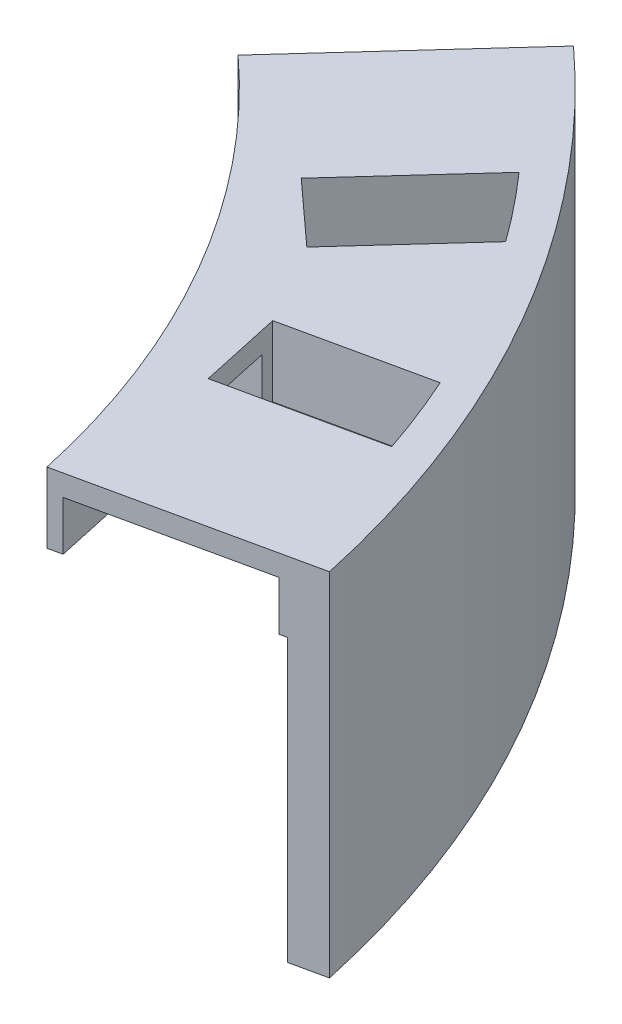
SolidWorks part; units mm, degrees
ref_plane "Front Plane" through (0, 0, 0) normal (0, 0, 1) x (1, 0, 0)
ref_plane "Top Plane" through (0, 0, 0) normal (0, 1, 0) x (1, 0, 0)
ref_plane "Right Plane" through (0, 0, 0) normal (1, 0, 0) x (0, 0, -1)
sketch "Sketch1" plane through (0, 157.2797, 0) normal (0, 1, 0) x (1, 0, 0)
  line L8 (293.0357, -316.1992) -> (265.929, -322.1104) construction
  line L9 (228.8196, -257.8351) -> (247.4922, -237.3156) construction
  line L10 (263.206, -252.2864) -> (248.4548, -268.4966) construction
  line L11 (248.4548, -268.4966) -> (257.3301, -276.573) construction
  line L12 (257.3301, -276.573) -> (270.7909, -261.7809) construction
  line L13 (283.4975, -283.7893) -> (263.9567, -288.0506) construction
  line L14 (263.9567, -288.0506) -> (266.5135, -299.7751) construction
  line L15 (266.5135, -299.7751) -> (287.9275, -295.1053) construction
  line L24 (293.0357, -316.1992) -> (265.929, -322.1104)
  line L25 (228.8196, -257.8351) -> (247.4922, -237.3156)
  line L26 (263.206, -252.2864) -> (248.4548, -268.4966)
  line L27 (248.4548, -268.4966) -> (257.3301, -276.573)
  line L28 (257.3301, -276.573) -> (270.7909, -261.7809)
  line L29 (283.4975, -283.7893) -> (263.9567, -288.0506)
  line L30 (263.9567, -288.0506) -> (266.5135, -299.7751)
  line L31 (266.5135, -299.7751) -> (287.9275, -295.1053)
  arc A0 (263.206, -252.2864) -> (247.4922, -237.3156) centre (169.4518, -334.9614) ccw construction
  arc A1 (283.4975, -283.7893) -> (270.7909, -261.7809) centre (169.4518, -334.9614) ccw construction
  arc A2 (293.0357, -316.1992) -> (287.9275, -295.1053) centre (169.4518, -334.9614) ccw construction
  arc A3 (263.206, -252.2864) -> (247.4922, -237.3156) centre (169.4518, -334.9614) ccw
  arc A4 (283.4975, -283.7893) -> (270.7909, -261.7809) centre (169.4518, -334.9614) ccw
  arc A5 (293.0357, -316.1992) -> (287.9275, -295.1053) centre (169.4518, -334.9614) ccw
  arc A6 (265.929, -322.1104) -> (228.8196, -257.8351) centre (146.6616, -348.1193) ccw
extrude "Boss-Extrude1" add sketch "Sketch1" along normal blind 10
sketch "Sketch2" plane through (0, 157.2797, 0) normal (0, 1, 0) x (1, 0, 0)
  line L0 (267.8229, -321.6974) -> (265.2661, -309.973)
  line L1 (293.0357, -316.1992) -> (265.929, -322.1104) construction
  line L2 (265.2661, -309.973) -> (295.5543, -303.368)
  line L3 (267.8229, -321.6974) -> (297.9305, -315.1318)
  line L4 (297.9305, -315.1318) -> (295.5543, -303.368)
  line L5 (228.8196, -257.8351) -> (247.4922, -237.3156) construction
  line L6 (251.0299, -233.428) -> (230.1657, -256.3559)
  line L7 (251.0299, -233.428) -> (259.9051, -241.5045)
  line L8 (259.9051, -241.5045) -> (239.041, -264.4323)
  line L9 (230.1657, -256.3559) -> (239.041, -264.4323)
  arc A1 (293.0357, -316.1992) -> (287.9275, -295.1053) centre (169.4518, -334.9614) ccw construction
  arc A3 (263.206, -252.2864) -> (247.4922, -237.3156) centre (169.4518, -334.9614) ccw construction
  dimension "D1" = 12
  dimension "D2" = 31
  dimension "D3" = 130
  dimension "D4" = 130
  dimension "D5" = 31
  dimension "D6" = 12
  dimension "D7" = 0
  dimension "D8" = 130
extrude "Cut-Extrude1" cut sketch "Sketch2" along normal blind 7
sketch "Sketch3" plane through (0, 167.2797, 0) normal (0, 1, 0) x (1, 0, 0)
  line L0 (293.0357, -316.1992) -> (298.8979, -314.9208)
  line L4 (251.5304, -232.878) -> (247.4922, -237.3156)
  arc A0 (251.5304, -232.878) -> (298.8979, -314.9208) centre (146.6616, -348.1193) cw
  arc A1 (248.1652, -236.576) -> (294.0127, -315.9862) centre (172.7112, -333.0795) cw construction
  arc A3 (247.4922, -237.3156) -> (293.0357, -316.1992) centre (169.4518, -334.9614) cw
  dimension "D5" = 122.5
  dimension "D1" = 6
  dimension "D2" = 6
  dimension "D3" = 1
  dimension "D4" = 1
  dimension "D6" = 6
extrude "Boss-Extrude2" add sketch "Sketch3" against normal blind 50
sketch "Sketch4" plane through (0, 117.2797, 0) normal (0, -1, 0) x (1, 0, 0)
  line L0 (293.0357, 316.1992) -> (294.0127, 315.9862)
  line L1 (293.0357, 316.1992) -> (298.8979, 314.9208) construction
  line L2 (247.4922, 237.3156) -> (248.1652, 236.576)
  line L3 (251.5304, 232.878) -> (247.4922, 237.3156) construction
  arc A0 (293.0357, 316.1992) -> (247.4922, 237.3156) centre (169.4518, 334.9614) cw
  arc A1 (248.1652, 236.576) -> (294.0127, 315.9862) centre (168.9131, 335.2723) ccw
  dimension "D1" = 1
  dimension "D2" = 1
extrude "Cut-Extrude2" cut sketch "Sketch4" against normal blind 40
sketch "Sketch5" plane through (0, 157.2797, 0) normal (0, 1, 0) x (1, 0, 0)
  line L0 (249.934, -269.8427) -> (255.8509, -275.227)
  line L1 (257.3301, -276.573) -> (248.4548, -268.4966) construction
  line L2 (249.934, -269.8427) -> (248.4548, -268.4966) construction
  line L3 (255.8509, -275.227) -> (257.3301, -276.573) construction
  line L4 (249.934, -269.8427) -> (243.2037, -277.2387)
  line L5 (255.8509, -275.227) -> (249.1205, -282.623)
  line L6 (243.2037, -277.2387) -> (249.1205, -282.623)
  line L7 (264.3828, -290.0047) -> (266.0873, -297.821)
  line L8 (266.5135, -299.7751) -> (263.9567, -288.0506) construction
  line L9 (263.9567, -288.0506) -> (264.3828, -290.0047) construction
  line L10 (266.0873, -297.821) -> (266.5135, -299.7751) construction
  line L11 (264.3828, -290.0047) -> (254.6125, -292.1353)
  line L12 (266.0873, -297.821) -> (256.317, -299.9517)
  line L13 (254.6125, -292.1353) -> (256.317, -299.9517)
  dimension "D1" = 8
  dimension "D2" = 10
  dimension "D3" = 10
  dimension "D4" = 8
  dimension "D5" = 10
  dimension "D6" = 10
extrude "Cut-Extrude3" cut sketch "Sketch5" along normal blind 7
